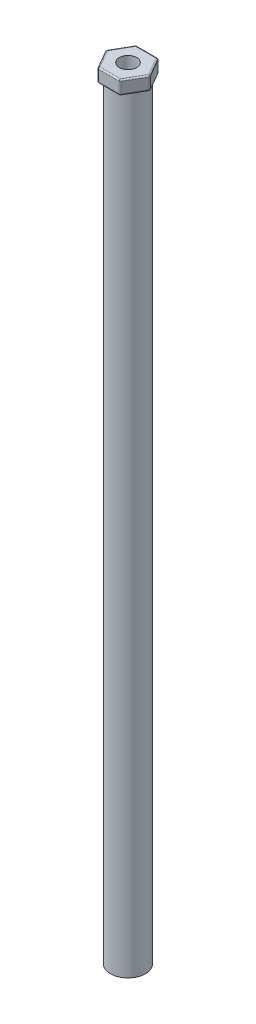
SolidWorks part; units mm, degrees
ref_plane "Front Plane" through (0, 0, 0) normal (0, 0, 1) x (1, 0, 0)
ref_plane "Top Plane" through (0, 0, 0) normal (0, 1, 0) x (1, 0, 0)
ref_plane "Right Plane" through (0, 0, 0) normal (1, 0, 0) x (0, 0, -1)
sketch "Sketch1" plane through (0, 0, 0) normal (0, 1, 0) x (1, 0, 0)
  circle A0 centre (0, 0) radius 6.35
  circle A1 centre (0, 0) radius 3.175
  dimension "D1" = 12.7
extrude "Boss-Extrude1" add sketch "Sketch1" along normal blind 279.4
ref_plane "Plane1" through (0, 139.7, 0) normal (0, 1, 0) x (1, 0, 0)
sketch "Sketch2" plane through (0, 279.4, 0) normal (0, 1, 0) x (1, 0, 0)
  line L1 (-8.0656, 0) -> (-4.0328, -6.985)
  line L2 (-4.0328, -6.985) -> (4.0328, -6.985)
  line L3 (4.0328, -6.985) -> (8.0656, 0)
  line L4 (8.0656, 0) -> (4.0328, 6.985)
  line L5 (4.0328, 6.985) -> (-4.0328, 6.985)
  line L6 (-4.0328, 6.985) -> (-8.0656, 0)
  circle A0 centre (0, 0) radius 6.985 construction
  circle A1 centre (0, 0) radius 3.175
  dimension "D1" = 13.97
extrude "Boss-Extrude2" add sketch "Sketch2" along normal blind 5
fillet "Fillet1" radius 0.5 18 edges at (6.0492, 279.4, -3.4925) (4.0328, 281.9, -6.985) (8.0656, 281.9, 0) (-4.0328, 281.9, -6.985) (-6.0492, 279.4, -3.4925) (-8.0656, 281.9, 0) (-6.0492, 279.4, 3.4925) (-4.0328, 281.9, 6.985) (0, 279.4, 6.985) (6.0492, 279.4, 3.4925) (4.0328, 281.9, 6.985) (6.0492, 284.4, 3.4925) (6.0492, 284.4, -3.4925) (0, 284.4, -6.985) (-6.0492, 284.4, -3.4925) (-6.0492, 284.4, 3.4925) (0, 284.4, 6.985) (0, 279.4, -6.985)
